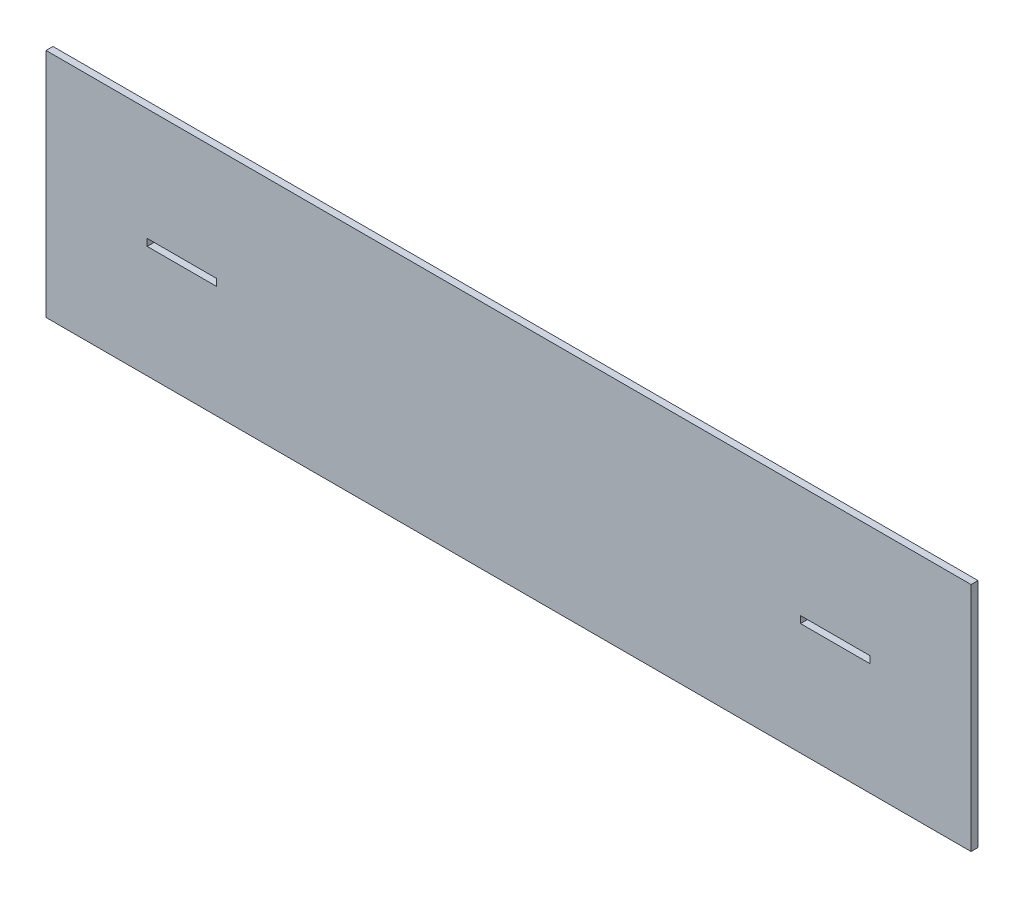
SolidWorks part; units mm, degrees
ref_plane "Alzado" through (0, 0, 0) normal (0, 0, 1) x (1, 0, 0)
ref_plane "Planta" through (0, 0, 0) normal (0, 1, 0) x (1, 0, 0)
ref_plane "Vista lateral" through (0, 0, 0) normal (1, 0, 0) x (0, 0, -1)
sketch "Croquis1" plane through (0, 0, 0) normal (0, 0, 1) x (1, 0, 0)
  line L0 (0, 50) -> (0, -50) construction
  line L1 (-200, 50) -> (200, 50)
  line L2 (-200, 50) -> (-200, -50)
  line L3 (-200, -50) -> (200, -50)
  line L4 (200, 50) -> (200, -50)
  line L5 (-200, 50) -> (200, -50) construction
  line L6 (-200, -50) -> (200, 50) construction
  line L7 (-200, 0) -> (200, 0) construction
  line L8 (156.24, 1.5) -> (156.24, -1.5)
  line L9 (-156.24, 1.5) -> (-126.24, 1.5)
  line L10 (-156.24, 1.5) -> (-156.24, -1.5)
  line L11 (-156.24, -1.5) -> (-126.24, -1.5)
  line L12 (-126.24, 1.5) -> (-126.24, -1.5)
  line L13 (-156.24, 1.5) -> (-126.24, -1.5) construction
  line L14 (-156.24, -1.5) -> (-126.24, 1.5) construction
  line L15 (156.24, -1.5) -> (126.24, -1.5)
  line L16 (126.24, 1.5) -> (126.24, -1.5)
  line L17 (156.24, 1.5) -> (126.24, 1.5)
  point P0 (0, 0)
  point P10 (-141.24, 0)
  dimension "D1" = 400
  dimension "D2" = 100
  dimension "D3" = 50
  dimension "D4" = 3
  dimension "D5" = 30
  dimension "D6" = 43.76
extrude "Saliente-Extruir1" add sketch "Croquis1" along normal blind 3
